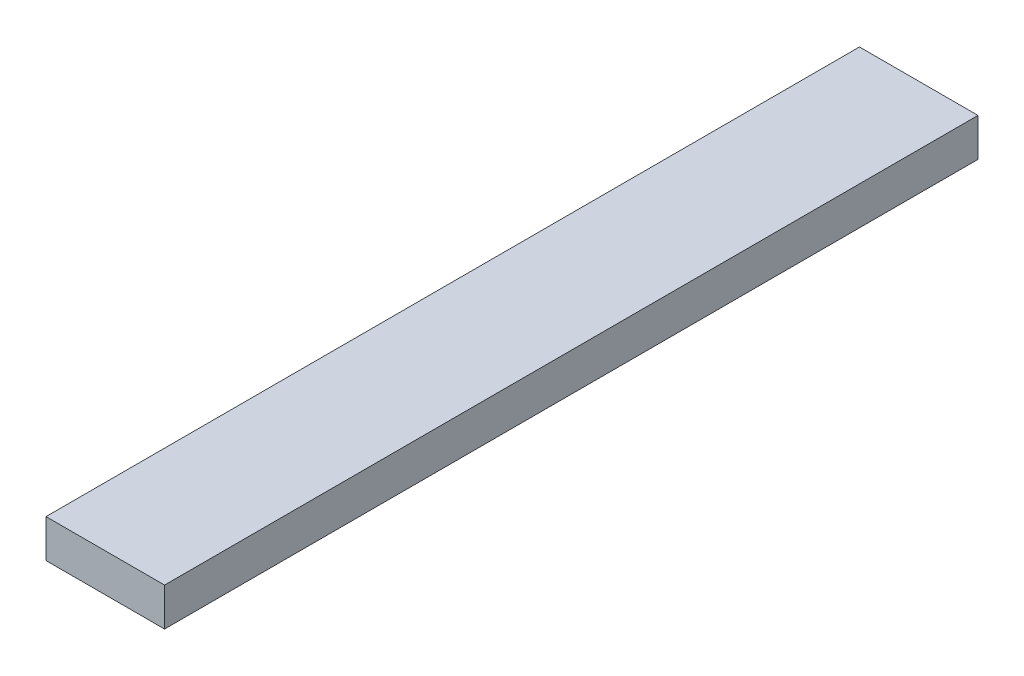
SolidWorks part; units mm, degrees
material "Balsa"
ref_plane "Front Plane" through (0, 0, 0) normal (0, 0, 1) x (1, 0, 0)
ref_plane "Top Plane" through (0, 0, 0) normal (0, 1, 0) x (1, 0, 0)
ref_plane "Right Plane" through (0, 0, 0) normal (1, 0, 0) x (0, 0, -1)
sketch "Sketch1" plane through (0, 0, 0) normal (0, 0, 1) x (1, 0, 0)
  line L1 (0, 0) -> (88.9, 0)
  line L2 (0, 0) -> (0, 28.575)
  line L3 (0, 28.575) -> (88.9, 28.575)
  line L4 (88.9, 0) -> (88.9, 28.575)
  dimension "D1" = 88.9
  dimension "D2" = 28.575
extrude "Boss-Extrude1" add sketch "Sketch1" along normal blind 610
